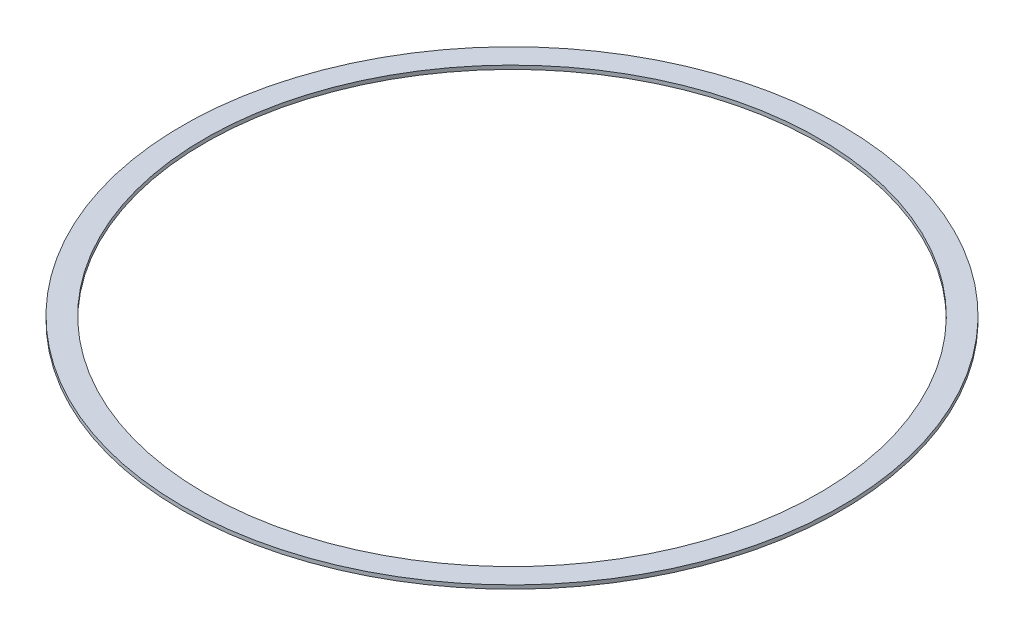
SolidWorks part; units mm, degrees
material "6061-T6 (SS)"
ref_plane "Front Plane" through (0, 0, 0) normal (0, 0, 1) x (1, 0, 0)
ref_plane "Top Plane" through (0, 0, 0) normal (0, 1, 0) x (1, 0, 0)
ref_plane "Right Plane" through (0, 0, 0) normal (1, 0, 0) x (0, 0, -1)
sketch "Sketch1" plane through (0, 0, 0) normal (0, 1, 0) x (1, 0, 0)
  circle A0 centre (0, 0) radius 223.8248
  circle A1 centre (0, 0) radius 208.5848
  dimension "D1" = 417.1696
  dimension "D2" = 447.6496
extrude "Boss-Extrude1" add sketch "Sketch1" along normal blind 2.54
ref_plane "Plane1" through (0, 1.27, 0) normal (0, 1, 0) x (1, 0, 0)
